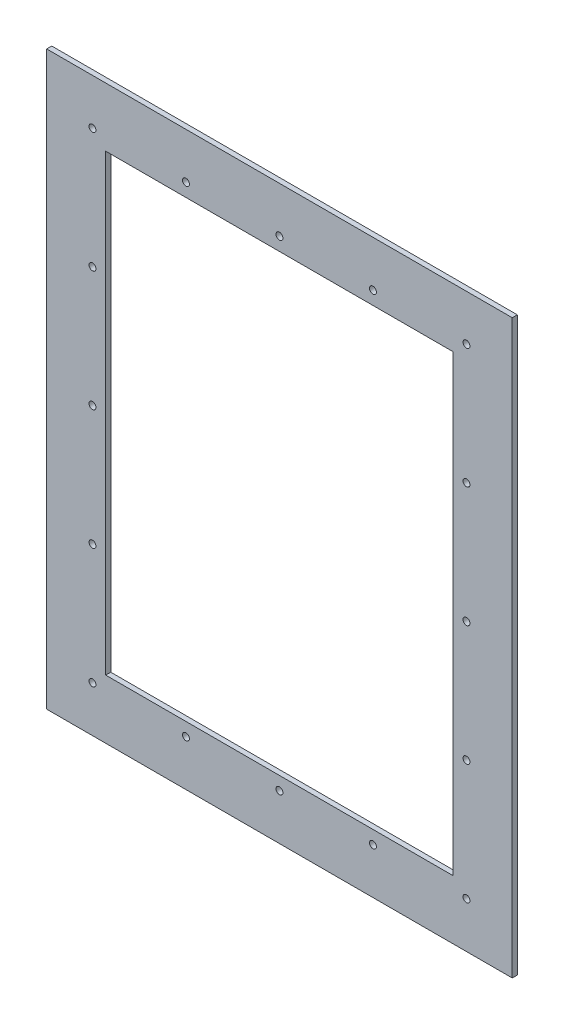
SolidWorks part; units mm, degrees
ref_plane "Front Plane" through (0, 0, 0) normal (0, 0, 1) x (1, 0, 0)
ref_plane "Top Plane" through (0, 0, 0) normal (0, 1, 0) x (1, 0, 0)
ref_plane "Right Plane" through (0, 0, 0) normal (1, 0, 0) x (0, 0, -1)
sketch "Sketch1" plane through (0, 0, 0) normal (0, 0, 1) x (1, 0, 0)
  line L0 (-103, 134.5) -> (103, -134.5) construction
  line L1 (-103, 134.5) -> (103, 134.5)
  line L2 (-103, 134.5) -> (-103, -134.5)
  line L3 (-103, -134.5) -> (103, -134.5)
  line L4 (103, 134.5) -> (103, -134.5)
  line L5 (-138, 169.5) -> (138, -169.5) construction
  line L6 (-138, 169.5) -> (138, 169.5)
  line L7 (-138, 169.5) -> (-138, -169.5)
  line L8 (-138, -169.5) -> (138, -169.5)
  line L9 (138, 169.5) -> (138, -169.5)
  line L10 (0, 134.5) -> (0, 169.5) construction
  line L11 (-103, 0) -> (-138, 0) construction
  line L12 (-103, 134.5) -> (-138, 169.5) construction
  line L13 (-55.4304, 142.3609) -> (0, 142.3609) construction
  line L14 (-110.8609, 142.3609) -> (-55.4304, 142.3609) construction
  line L15 (-110.8609, 142.3609) -> (-110.8609, 0) construction
  line L16 (0, 142.3609) -> (0, 134.5) construction
  line L17 (-110.8609, 0) -> (-103, 0) construction
  circle A0 centre (-110.8609, 142.3609) radius 2.05
  circle A1 centre (-55.4304, 142.3609) radius 2.05
  circle A2 centre (-110.8609, 71.1804) radius 2.05
  circle A3 centre (-55.4304, -142.3609) radius 2.05
  circle A4 centre (-110.8609, -142.3609) radius 2.05
  circle A5 centre (-110.8609, -71.1804) radius 2.05
  circle A6 centre (55.4304, 142.3609) radius 2.05
  circle A7 centre (110.8609, 142.3609) radius 2.05
  circle A8 centre (110.8609, 71.1804) radius 2.05
  circle A9 centre (55.4304, -142.3609) radius 2.05
  circle A10 centre (110.8609, -142.3609) radius 2.05
  circle A11 centre (110.8609, -71.1804) radius 2.05
  circle A12 centre (-110.8609, 0) radius 2.05
  circle A13 centre (110.8609, 0) radius 2.05
  circle A14 centre (0, 142.3609) radius 2.05
  circle A15 centre (0, -142.3609) radius 2.05
  dimension "D4" = 4.1
  dimension "D1" = 206
  dimension "D2" = 269
  dimension "D3" = 35
extrude "Boss-Extrude1" add sketch "Sketch1" along normal blind 3
equation "\"D2@Sketch1\"=279-10"
equation "\"D1@Sketch1\"=216-10"
